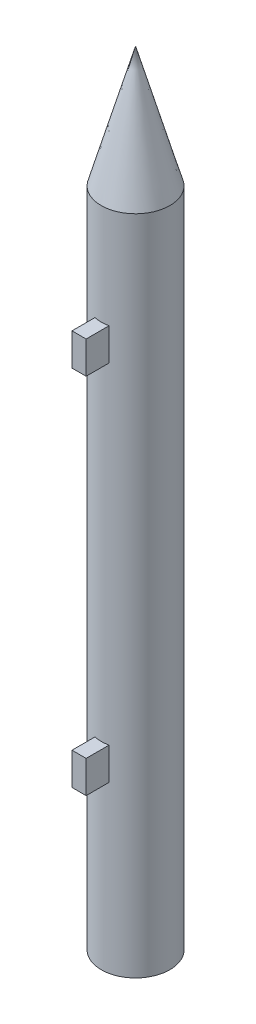
SolidWorks part; units mm, degrees
ref_plane "Front Plane" through (0, 0, 0) normal (0, 0, 1) x (1, 0, 0)
ref_plane "Top Plane" through (0, 0, 0) normal (0, 1, 0) x (1, 0, 0)
ref_plane "Right Plane" through (0, 0, 0) normal (1, 0, 0) x (0, 0, -1)
sketch "Sketch1" plane through (0, 0, 0) normal (0, 0, 1) x (1, 0, 0)
  line L0 (0, 0) -> (0, 320) construction
  line L1 (0, 320) -> (6, 305)
  line L2 (6, 305) -> (15.7241, 280.6897)
  line L3 (15.7241, 280.6897) -> (21, 250)
  line L4 (21, 250) -> (26.1241, 220.1932)
  line L5 (26.1241, 220.1932) -> (26.1241, 165)
  line L6 (26.1241, 165) -> (26.2, 163)
  line L7 (26.2, 163) -> (26.2, 157)
  line L8 (26.2, 157) -> (25, 155)
  line L9 (25, 155) -> (25, 60)
  line L10 (25, 60) -> (21, 35)
  line L11 (21, 35) -> (10.3456, 27.2847)
  line L12 (10.3456, 27.2847) -> (21, 0)
  line L13 (21, 0) -> (19.7931, 3.0907)
  line L14 (19.7931, 3.0907) -> (10.3456, 27.2847)
  line L15 (10.3456, 27.2847) -> (0, 27.2847)
  line L16 (0, 27.2847) -> (0, 320)
sketch "Sketch2" plane through (0, 0, 0) normal (1, 0, 0) x (0, 0, -1)
  line L0 (34, 6) -> (34, 200) construction
  line L1 (34, 200) -> (42.5, 170)
  line L2 (42.5, 170) -> (42.5, 20)
  line L3 (42.5, 20) -> (42.5, 10)
  line L4 (42.5, 10) -> (42.5, 6)
  line L5 (42.5, 6) -> (34, 6)
  line L6 (34, 6) -> (34, 200)
revolve "Revolve2" add sketch "Sketch2" angle 360 about L0
sketch "Sketch3" plane through (0, 0, 0) normal (1, 0, 0) x (0, 0, -1)
  line L0 (20, 145) -> (34, 145)
  line L1 (34, 145) -> (34, 137)
  line L2 (34, 137) -> (20, 137)
  line L3 (20, 137) -> (20, 145)
  line L4 (20, 55) -> (34, 55)
  line L5 (34, 55) -> (34, 47)
  line L6 (34, 47) -> (20, 47)
  line L7 (20, 47) -> (20, 55)
extrude "Boss-Extrude2" add sketch "Sketch3" along normal mid plane 3.5
sketch "Sketch4" plane through (0, 0, 0) normal (0, 0, 1) x (1, 0, 0)
  line L0 (0, 320) -> (0, 350) construction
  line L1 (0, 350) -> (0, 320)
  line L2 (0, 320) -> (0, 350)
